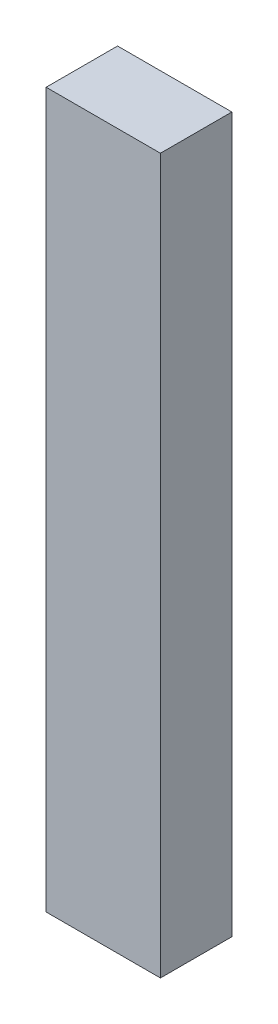
SolidWorks part; units mm, degrees
ref_plane "前视基准面" through (0, 0, 0) normal (0, 0, 1) x (1, 0, 0)
ref_plane "上视基准面" through (0, 0, 0) normal (0, 1, 0) x (1, 0, 0)
ref_plane "右视基准面" through (0, 0, 0) normal (1, 0, 0) x (0, 0, -1)
sketch "草图2" plane through (-5, 0, 0) normal (1, 0, 0) x (0, 0, -1)
  line L1 (49, -25) -> (1, -25) construction
  line L2 (0, 475) -> (50, 475)
  line L3 (0, 475) -> (0, -25)
  line L4 (0, -25) -> (50, -25)
  line L5 (50, 475) -> (50, -25)
  line L6 (50, 24) -> (50, -24) construction
  line L7 (0, -24) -> (0, 24) construction
  line L9 (1, 475) -> (49, 475) construction
extrude "拉伸-薄壁1" add sketch "草图2" along normal blind 80 thin
sketch "草图3" plane through (75, 0, 0) normal (1, 0, 0) x (0, 0, -1)
  line L4 (0, 475) -> (0, -25)
  line L5 (0, -25) -> (50, -25)
  line L6 (50, -25) -> (50, 475)
  line L7 (50, 475) -> (0, 475)
  line L8 (0, 475) -> (0, -25)
  line L9 (0, -25) -> (50, -25)
  line L10 (50, -25) -> (50, 475)
  line L11 (50, 475) -> (0, 475)
  dimension "D1" = 0
extrude "凸台-拉伸1" add sketch "草图3" against normal blind 2
